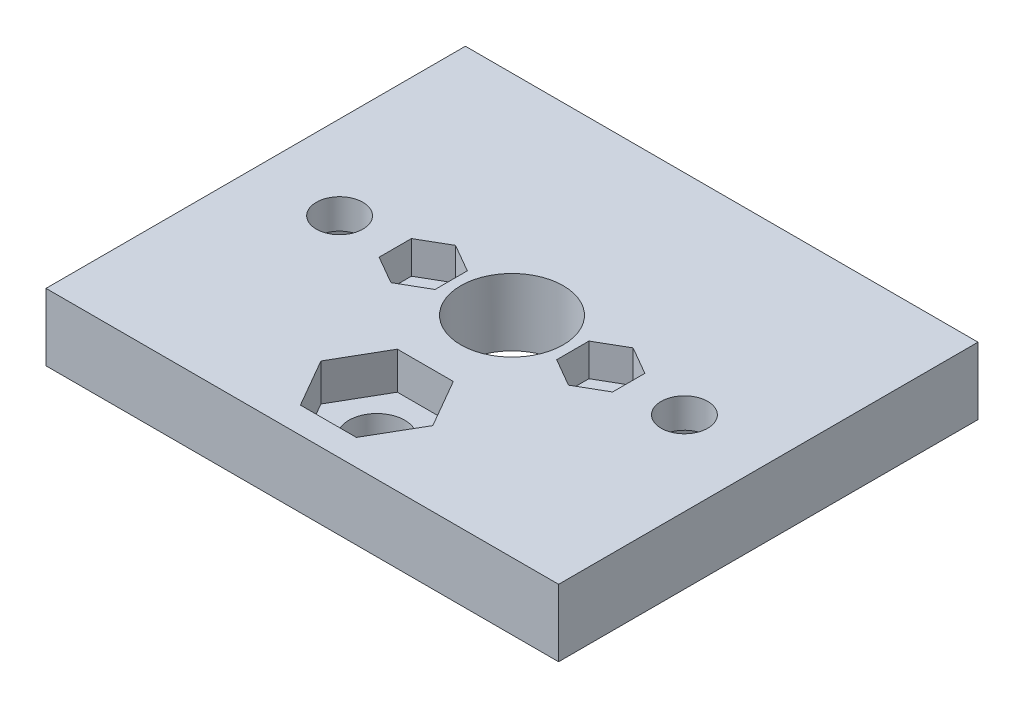
SolidWorks part; units mm, degrees
ref_plane "Front Plane" through (0, 0, 0) normal (0, 0, 1) x (1, 0, 0)
ref_plane "Top Plane" through (0, 0, 0) normal (0, 1, 0) x (1, 0, 0)
ref_plane "Right Plane" through (0, 0, 0) normal (1, 0, 0) x (0, 0, -1)
sketch "Sketch1" plane through (0, 0, 0) normal (0, 1, 0) x (1, 0, 0)
  line L1 (-27.5, -22.5) -> (27.5, -22.5)
  line L2 (-27.5, -22.5) -> (-27.5, 22.5)
  line L3 (-27.5, 22.5) -> (27.5, 22.5)
  line L4 (27.5, -22.5) -> (27.5, 22.5)
  line L5 (-27.5, -22.5) -> (27.5, 22.5) construction
  line L6 (-27.5, 22.5) -> (27.5, -22.5) construction
  point P0 (0, 0)
  dimension "D1" = 55
  dimension "D2" = 45
extrude "Boss-Extrude1" add sketch "Sketch1" along normal blind 7.2
sketch "Sketch2" plane through (0, 7.2, 0) normal (0, 1, 0) x (1, 0, 0)
  circle A0 centre (0, 0) radius 5.5
  circle A1 centre (0, 0) radius 18.5 construction
  circle A2 centre (-18.5, 0) radius 2.5
  circle A3 centre (18.5, 0) radius 2.5
  circle A4 centre (0, 0) radius 9.525 construction
  circle A5 centre (-9.525, 0) radius 1.5
  circle A6 centre (9.525, 0) radius 1.5
  dimension "D1" = 11
  dimension "D2" = 37
  dimension "D3" = 5
  dimension "D5" = 19.05
  dimension "D6" = 3
extrude "Cut-Extrude1" cut sketch "Sketch2" against normal through all both and the other way through all
sketch "Sketch3" plane through (0, 7.2, 0) normal (0, 1, 0) x (1, 0, 0)
  line L0 (-27.5, 22.5) -> (-27.5, -22.5) construction
  line L1 (-9.525, 3.4641) -> (-12.525, 1.7321)
  line L2 (-12.525, 1.7321) -> (-12.525, -1.7321)
  line L3 (-12.525, -1.7321) -> (-9.525, -3.4641)
  line L4 (-9.525, -3.4641) -> (-6.525, -1.7321)
  line L5 (-6.525, -1.7321) -> (-6.525, 1.7321)
  line L6 (-6.525, 1.7321) -> (-9.525, 3.4641)
  line L7 (9.525, 3.4641) -> (6.525, 1.7321)
  line L8 (6.525, 1.7321) -> (6.525, -1.7321)
  line L9 (6.525, -1.7321) -> (9.525, -3.4641)
  line L10 (9.525, -3.4641) -> (12.525, -1.7321)
  line L11 (12.525, -1.7321) -> (12.525, 1.7321)
  line L12 (12.525, 1.7321) -> (9.525, 3.4641)
  circle A0 centre (-9.525, 0) radius 3 construction
  circle A1 centre (9.525, 0) radius 3 construction
  dimension "D1" = 6
  dimension "D2" = 6
extrude "Cut-Extrude2" cut sketch "Sketch3" against normal blind 3.5
sketch "Sketch5" plane through (0, 0, 0) normal (0, -1, 0) x (1, 0, 0)
  line L0 (27.5, -22.5) -> (-27.5, -22.5) construction
  line L1 (23.3497, 0) -> (20.9249, 4.2)
  line L2 (20.9249, 4.2) -> (16.0751, 4.2)
  line L3 (16.0751, 4.2) -> (13.6503, 0)
  line L4 (13.6503, 0) -> (16.0751, -4.2)
  line L5 (16.0751, -4.2) -> (20.9249, -4.2)
  line L6 (20.9249, -4.2) -> (23.3497, 0)
  line L7 (-13.6503, 0) -> (-16.0751, 4.2)
  line L8 (-16.0751, 4.2) -> (-20.9249, 4.2)
  line L9 (-20.9249, 4.2) -> (-23.3497, 0)
  line L10 (-23.3497, 0) -> (-20.9249, -4.2)
  line L11 (-20.9249, -4.2) -> (-16.0751, -4.2)
  line L12 (-16.0751, -4.2) -> (-13.6503, 0)
  circle A0 centre (18.5, 0) radius 4.2 construction
  circle A1 centre (-18.5, 0) radius 4.2 construction
  dimension "D1" = 8.4
  dimension "D2" = 8.4
extrude "Cut-Extrude3" cut sketch "Sketch5" against normal blind 4
sketch "Sketch7" plane through (0, 7.2, 0) normal (0, 1, 0) x (1, 0, 0)
  line L0 (0, 22.5) -> (0, -22.5) construction
  line L1 (27.5, 22.5) -> (-27.5, 22.5) construction
  line L2 (-27.5, -22.5) -> (27.5, -22.5) construction
  circle A0 centre (0, -14.5) radius 3
  dimension "D1" = 6
  dimension "D2" = 8
extrude "Cut-Extrude4" cut sketch "Sketch7" against normal through all both and the other way through all
sketch "Sketch8" plane through (0, 7.2, 0) normal (0, 1, 0) x (1, 0, 0)
  line L0 (-27.5, -22.5) -> (27.5, -22.5) construction
  line L1 (6.0044, -14.5) -> (3.0022, -9.3)
  line L2 (3.0022, -9.3) -> (-3.0022, -9.3)
  line L3 (-3.0022, -9.3) -> (-6.0044, -14.5)
  line L4 (-6.0044, -14.5) -> (-3.0022, -19.7)
  line L5 (-3.0022, -19.7) -> (3.0022, -19.7)
  line L6 (3.0022, -19.7) -> (6.0044, -14.5)
  circle A0 centre (0, -14.5) radius 5.2 construction
  dimension "D1" = 10.4
extrude "Cut-Extrude5" cut sketch "Sketch8" against normal blind 4
